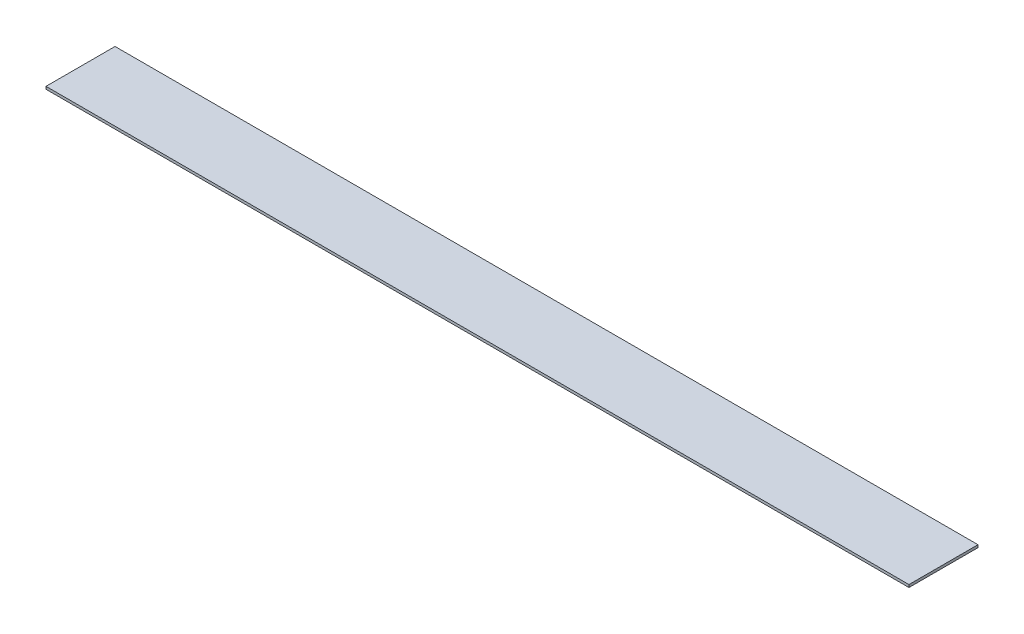
SolidWorks part; units mm, degrees
material "Плата системы питания"
ref_plane "Спереди" through (0, 0, 0) normal (0, 0, 1) x (1, 0, 0)
ref_plane "Сверху" through (0, 0, 0) normal (0, 1, 0) x (1, 0, 0)
ref_plane "Справа" through (0, 0, 0) normal (1, 0, 0) x (0, 0, -1)
sketch "Эскиз1" plane through (0, 0, 0) normal (0, 1, 0) x (1, 0, 0)
  line L1 (-250, 20) -> (250, 20)
  line L2 (-250, 20) -> (-250, -20)
  line L3 (-250, -20) -> (250, -20)
  line L4 (250, 20) -> (250, -20)
extrude "Бобышка-Вытянуть1" add sketch "Эскиз1" along normal blind 1.5
